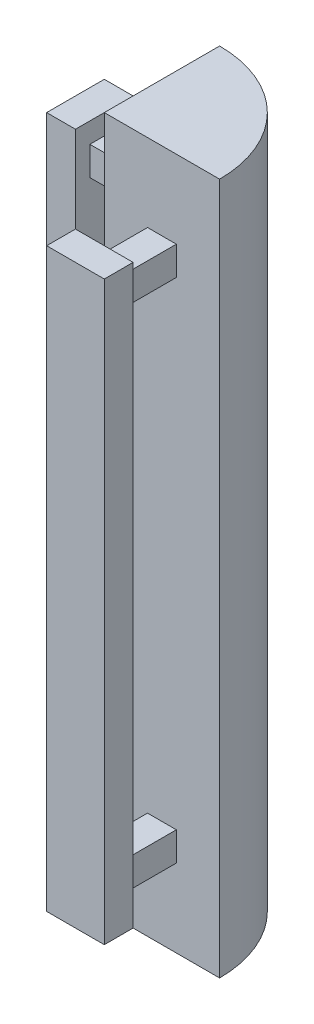
SolidWorks part; units mm, degrees
ref_plane "Front Plane" through (0, 0, 0) normal (0, 0, 1) x (1, 0, 0)
ref_plane "Top Plane" through (0, 0, 0) normal (0, 1, 0) x (1, 0, 0)
ref_plane "Right Plane" through (0, 0, 0) normal (1, 0, 0) x (0, 0, -1)
sketch "Sketch1" plane through (0, 0, 0) normal (0, 1, 0) x (1, 0, 0)
  line L1 (0, 0) -> (38.1, 0)
  line L2 (0, 0) -> (0, 101.6)
  line L3 (0, 101.6) -> (38.1, 101.6)
  line L4 (38.1, 0) -> (38.1, 101.6)
  line L5 (38.1, 101.6) -> (12.7, 101.6)
  line L6 (38.1, 101.6) -> (38.1, 76.2)
  line L7 (38.1, 76.2) -> (12.7, 76.2)
  line L8 (12.7, 101.6) -> (12.7, 76.2)
  arc A0 (38.1, 76.2) -> (12.7, 101.6) centre (12.7, 76.2) ccw
  dimension "D3" = 25.4
  dimension "D1" = 38.1
  dimension "D2" = 101.6
  dimension "D4" = 25.4
extrude "Boss-Extrude1" add sketch "Sketch1" along normal blind 304.8 contours L3 L2 L1 L4
sketch "Sketch2" plane through (0, 0, 0) normal (0, -1, 0) x (1, 0, 0)
  line L0 (38.1, -101.6) -> (38.1, -76.2) construction
  line L1 (38.1, -101.6) -> (12.7, -101.6) construction
  line L2 (12.7, -101.6) -> (12.7, -76.2) construction
  line L3 (38.1, -76.2) -> (12.7, -76.2) construction
  line L4 (38.1, 0) -> (38.1, -101.6) construction
  line L5 (0, 0) -> (38.1, 0) construction
  line L6 (0, 0) -> (0, -101.6) construction
  line L7 (0, -101.6) -> (38.1, -101.6) construction
  line L8 (38.1, -101.6) -> (38.1, -76.2)
  line L9 (38.1, -101.6) -> (12.7, -101.6)
  line L10 (12.7, -101.6) -> (12.7, -76.2)
  line L11 (38.1, -76.2) -> (12.7, -76.2)
  line L12 (38.1, 0) -> (38.1, -101.6)
  line L13 (0, 0) -> (38.1, 0)
  line L14 (0, 0) -> (0, -101.6)
  line L15 (0, -101.6) -> (38.1, -101.6)
  line L16 (38.1, -76.2) -> (0, -76.2)
  arc A0 (12.7, -101.6) -> (38.1, -76.2) centre (12.7, -76.2) ccw construction
  arc A1 (12.7, -101.6) -> (38.1, -76.2) centre (12.7, -76.2) ccw
  line M5 (38.1, -101.6) -> (38.1, 0)
  line M6 (38.1, 0) -> (0, 0)
  line M7 (0, 0) -> (0, -101.6)
extrude "Cut-Extrude2" cut sketch "Sketch2" against normal through all contours L16 L11 M5 M6 M7
sketch "Sketch3" plane through (0, 0, 0) normal (0, -1, 0) x (1, 0, 0)
  line L0 (12.7, -101.6) -> (12.7, -76.2) construction
  line L1 (12.7, -101.6) -> (12.7, -76.2)
  line L4 (38.1, -101.6) -> (38.1, -76.2)
  line L5 (38.1, -76.2) -> (0, -76.2)
  line L6 (0, -76.2) -> (0, -101.6)
  line L7 (0, -101.6) -> (38.1, -101.6)
  line L8 (38.1, -101.6) -> (38.1, -76.2)
  line L9 (38.1, -76.2) -> (0, -76.2)
  line L10 (0, -76.2) -> (0, -101.6)
  line L11 (0, -101.6) -> (38.1, -101.6)
  line M6 (38.1, -76.2) -> (0, -76.2)
  line M7 (0, -76.2) -> (0, -101.6)
  line M8 (0, -101.6) -> (38.1, -101.6)
  dimension "D1" = 0
extrude "Cut-Extrude3" cut sketch "Sketch3" against normal through all contours L1 M8 M6 M7
sketch "Sketch4" plane through (0, 0, 0) normal (0, -1, 0) x (1, 0, 0)
  line L0 (38.1, -101.6) -> (38.1, -76.2) construction
  line L1 (38.1, -101.6) -> (12.7, -101.6) construction
  line L2 (12.7, -101.6) -> (12.7, -76.2) construction
  line L3 (38.1, -76.2) -> (12.7, -76.2) construction
  line L4 (12.7, -76.2) -> (12.7, -101.6)
  line L5 (12.7, -101.6) -> (38.1, -101.6)
  line L6 (38.1, -101.6) -> (38.1, -76.2)
  line L7 (38.1, -76.2) -> (12.7, -76.2)
  line L8 (12.7, -76.2) -> (12.7, -101.6)
  line L9 (12.7, -101.6) -> (38.1, -101.6)
  line L10 (38.1, -101.6) -> (38.1, -76.2)
  line L11 (38.1, -76.2) -> (12.7, -76.2)
  line L12 (38.1, 0) -> (38.1, -101.6) construction
  line L13 (0, 0) -> (38.1, 0) construction
  line L14 (0, 0) -> (0, -101.6) construction
  line L15 (0, -101.6) -> (38.1, -101.6) construction
  line L16 (38.1, -101.6) -> (38.1, -76.2)
  line L17 (38.1, -101.6) -> (12.7, -101.6)
  line L18 (12.7, -101.6) -> (12.7, -76.2)
  line L19 (38.1, -76.2) -> (12.7, -76.2)
  line L20 (38.1, 0) -> (38.1, -101.6)
  line L21 (0, 0) -> (38.1, 0)
  line L22 (0, 0) -> (0, -101.6)
  line L23 (0, -101.6) -> (38.1, -101.6)
  arc A0 (12.7, -101.6) -> (38.1, -76.2) centre (12.7, -76.2) ccw construction
  arc A1 (12.7, -101.6) -> (38.1, -76.2) centre (12.7, -76.2) ccw
  arc A2 (12.7, -101.6) -> (38.1, -76.2) centre (12.7, -76.2) ccw
  line M7 (12.7, -101.6) -> (38.1, -101.6)
  line M8 (38.1, -101.6) -> (38.1, -76.2)
  dimension "D1" = 0
extrude "Cut-Extrude4" cut sketch "Sketch4" against normal through all contours A1 M7 M8
sketch "Sketch5" plane through (0, 0, 0) normal (0, -1, 0) x (1, 0, 0)
  line L2 (12.7, -76.2) -> (12.7, -101.6)
  line L3 (38.1, -76.2) -> (12.7, -76.2)
  line L4 (12.7, -76.2) -> (12.7, -101.6)
  line L5 (38.1, -76.2) -> (12.7, -76.2)
  arc A1 (12.7, -101.6) -> (38.1, -76.2) centre (12.7, -76.2) ccw
  arc A2 (12.7, -101.6) -> (38.1, -76.2) centre (12.7, -76.2) ccw
  dimension "D1" = 0
extrude "Cut-Extrude5" cut sketch "Sketch5" against normal blind 152.4
sketch "Sketch6" plane through (12.7, 0, 0) normal (-1, 0, 0) x (0, 0, 1)
  line L0 (-88.9, 304.8) -> (-88.9, 152.4) construction
  line L2 (-92.075, 287.6331) -> (-85.725, 287.6331)
  line L3 (-92.075, 287.6331) -> (-92.075, 281.2831)
  line L4 (-101.6, 152.4) -> (-76.2, 152.4)
  line L5 (-76.2, 152.4) -> (-76.2, 304.8)
  line L6 (-76.2, 304.8) -> (-101.6, 304.8)
  line L7 (-101.6, 304.8) -> (-101.6, 152.4)
  line L8 (-101.6, 152.4) -> (-76.2, 152.4)
  line L9 (-76.2, 152.4) -> (-76.2, 304.8)
  line L10 (-76.2, 304.8) -> (-101.6, 304.8)
  line L11 (-101.6, 304.8) -> (-101.6, 152.4)
  line L12 (-92.075, 281.2831) -> (-85.725, 281.2831)
  line L13 (-85.725, 287.6331) -> (-85.725, 281.2831)
  line L14 (-92.075, 287.6331) -> (-85.725, 281.2831) construction
  line L15 (-92.075, 281.2831) -> (-85.725, 287.6331) construction
  point P6 (-88.9, 284.4581)
  dimension "D2" = 6.35
  dimension "D3" = 6.35
  dimension "D1" = 0
extrude "Boss-Extrude2" add sketch "Sketch6" along normal blind 12.7 contours L13 L2 L3 L12
ref_plane "Plane1" through (0, 228.6, 0) normal (0, -1, 0) x (-1, 0, 0)
mirror "Mirror1" about plane through (0, 228.6, 0) normal (0, -1, 0) of "Boss-Extrude2"
sketch "Sketch7" plane through (0, 0, 0) normal (-1, 0, 0) x (0, 0, 1)
  line L0 (-92.075, 287.6331) -> (-85.725, 281.2831) construction
  line L1 (-92.075, 175.9169) -> (-85.725, 169.5669) construction
  line L2 (-88.9, 172.7419) -> (-88.9, 284.4581)
  line L4 (-95.25, 292.1) -> (-82.55, 292.1)
  line L5 (-95.25, 292.1) -> (-95.25, 165.1)
  line L6 (-95.25, 165.1) -> (-82.55, 165.1)
  line L7 (-82.55, 292.1) -> (-82.55, 165.1)
  line L8 (-95.25, 292.1) -> (-82.55, 165.1) construction
  line L9 (-95.25, 165.1) -> (-82.55, 292.1) construction
  point P10 (-88.9, 228.6)
  dimension "D1" = 12.7
  dimension "D2" = 127
extrude "Boss-Extrude3" add sketch "Sketch7" along normal blind 6.35
ref_plane "Plane2" through (-31.75, 0, -31.75) normal (0.7071, 0, 0.7071) x (0.7071, 0, -0.7071)
mirror "Mirror2" about plane through (-31.75, 0, -31.75) normal (0.7071, 0, 0.7071) of "Boss-Extrude3", "Mirror1", "Boss-Extrude2"
